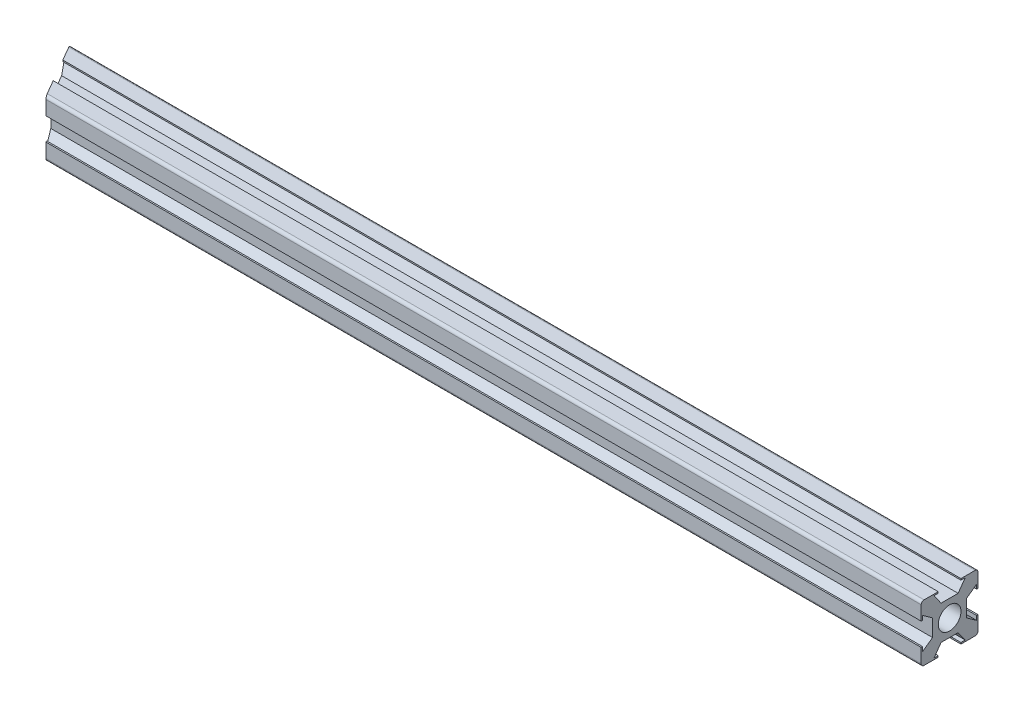
SolidWorks part; units mm, degrees
ref_plane "前视基准面" through (0, 0, 0) normal (0, 0, 1) x (1, 0, 0)
ref_plane "上视基准面" through (0, 0, 0) normal (0, 1, 0) x (1, 0, 0)
ref_plane "右视基准面" through (0, 0, 0) normal (1, 0, 0) x (0, 0, -1)
sketch "草图1" plane through (0, 0, 0) normal (0, 0, 1) x (1, 0, 0)
  line L1 (-66.5187, -1.3979) -> (253.4813, -1.3979)
  line L2 (-66.5187, -1.3979) -> (-66.5187, -11.3979)
  line L3 (-66.5187, -11.3979) -> (253.4813, -11.3979)
  line L4 (253.4813, -1.3979) -> (253.4813, -11.3979)
  dimension "D1" = 10
  dimension "D2" = 320
extrude "凸台-拉伸1" add sketch "草图1" along normal blind 10
sketch "草图2" plane through (253.4813, 0, 0) normal (1, 0, 0) x (0, 0, -1)
  circle A0 centre (0, -11.3979) radius 4
  dimension "D1" = 8
extrude "切除-拉伸1" cut sketch "草图2" against normal blind 1270
sketch "草图3" plane through (253.4813, 0, 0) normal (1, 0, 0) x (0, 0, -1)
  line L0 (-4, -1.3979) -> (0, -1.3979)
  line L1 (-10, -11.3979) -> (-10, -1.3979) construction
  line L2 (-10, -1.3979) -> (0, -1.3979) construction
  line L3 (-10, -7.3979) -> (-10, -11.3979)
  line L4 (-4, -1.3979) -> (-4, -1.8979)
  line L5 (-4, -1.8979) -> (-5.5, -1.8979)
  line L6 (-3, -5.3979) -> (0, -5.3979)
  line L7 (0, -7.3979) -> (0, -1.3979) construction
  line L8 (0, -5.3979) -> (0, -1.3979)
  line L9 (-10, -11.3979) -> (-6, -11.3979)
  line L10 (-10, -11.3979) -> (-4, -11.3979) construction
  line L11 (-6, -11.3979) -> (-6, -8.3979)
  line L12 (-10, -7.3979) -> (-9.5, -7.3979)
  line L13 (-9.5, -7.3979) -> (-9.5, -5.8979)
  line L14 (-5.5, -1.8979) -> (-3, -5.3979)
  line L15 (-9.5, -5.8979) -> (-6, -8.3979)
  dimension "D1" = 4
  dimension "D2" = 4
  dimension "D3" = 4
  dimension "D4" = 4
  dimension "D5" = 0.5
  dimension "D6" = 0.5
  dimension "D7" = 3
  dimension "D8" = 3
  dimension "D9" = 1.5
  dimension "D10" = 1.5
extrude "切除-拉伸2" cut sketch "草图3" against normal blind 1270
fillet "圆角1" radius 1 1 edges at (93.4813, -1.3979, 10)
pattern_circular "阵列(圆周)2" count 4 every 90 about axis through (0, -11.3979, 0) along (1, 0, 0) of "凸台-拉伸1", "圆角1", "切除-拉伸1", "切除-拉伸2"
sketch "草图5" plane through (0, -21.3979, 0) normal (0, -1, 0) x (1, 0, 0)
  line L0 (-78.2027, 13.0817) -> (-42.998, 30.3252)
  line L1 (-78.2027, 13.0817) -> (-66.4821, -10.3506)
  line L3 (-66.4821, -10.3506) -> (-42.998, 30.3252)
  dimension "D2" = 56.574
extrude "切除-拉伸4" cut sketch "草图5" against normal blind 24
